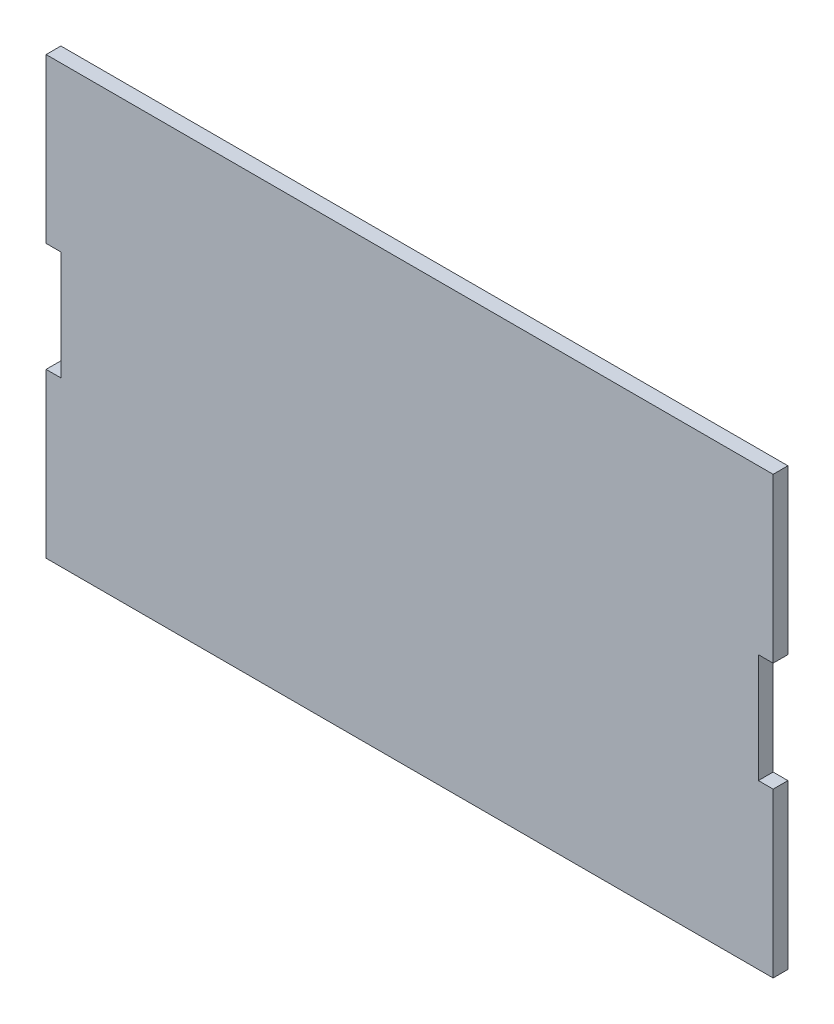
SolidWorks part; units mm, degrees
ref_plane "Front Plane" through (0, 0, 0) normal (0, 0, 1) x (1, 0, 0)
ref_plane "Top Plane" through (0, 0, 0) normal (0, 1, 0) x (1, 0, 0)
ref_plane "Right Plane" through (0, 0, 0) normal (1, 0, 0) x (0, 0, -1)
sketch "Sketch1" plane through (0, 0, 0) normal (0, 0, 1) x (1, 0, 0)
  line L0 (0, 0) -> (0, 150) construction
  line L1 (-250, -150) -> (250, -150)
  line L2 (-250, -150) -> (-250, -37.5)
  line L3 (-250, 150) -> (250, 150)
  line L4 (250, -150) -> (250, -37.5)
  line L5 (-250, -150) -> (250, 150) construction
  line L6 (-250, 150) -> (250, -150) construction
  line L7 (239.84, -37.5) -> (250, -37.5)
  line L8 (239.84, -37.5) -> (239.84, 37.5)
  line L9 (239.84, 37.5) -> (250, 37.5)
  line L11 (250, 37.5) -> (250, 150)
  line L12 (239.84, 0) -> (0, 0) construction
  line L13 (-239.84, -37.5) -> (-250, -37.5)
  line L14 (-239.84, -37.5) -> (-239.84, 37.5)
  line L15 (-239.84, 37.5) -> (-250, 37.5)
  line L16 (-250, 37.5) -> (-250, 150)
  point P0 (0, 0)
  point P5 (250, 0)
  dimension "D1" = 300
  dimension "D2" = 500
  dimension "D3" = 10.16
  dimension "D4" = 75
extrude "Boss-Extrude1" add sketch "Sketch1" along normal blind 10.16
